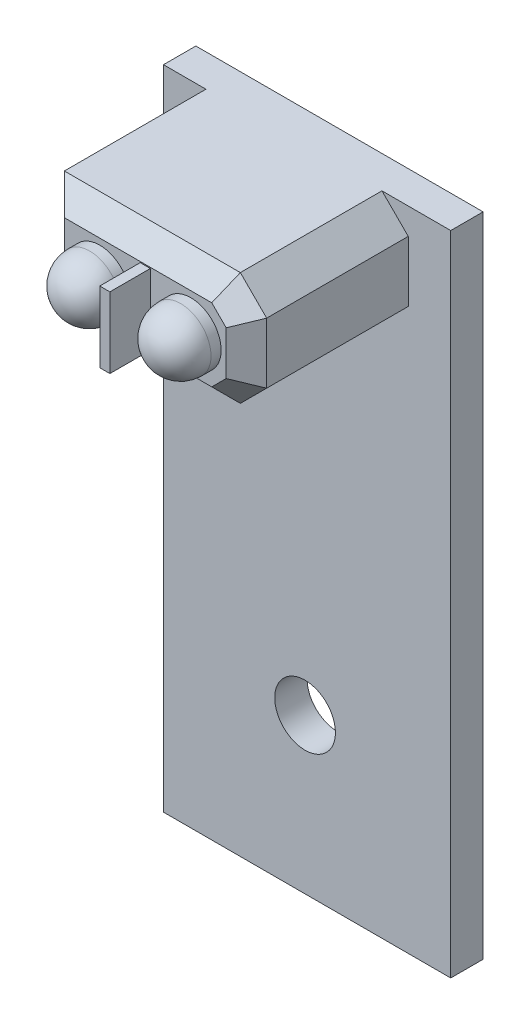
SolidWorks part; units mm, degrees
ref_plane "Alzado" through (0, 0, 0) normal (0, 0, 1) x (1, 0, 0)
ref_plane "Planta" through (0, 0, 0) normal (0, 1, 0) x (1, 0, 0)
ref_plane "Vista lateral" through (0, 0, 0) normal (1, 0, 0) x (0, 0, -1)
sketch "Croquis1" plane through (0, 0, 0) normal (0, 0, 1) x (1, 0, 0)
  line L1 (-7.1, -16) -> (7.1, -16)
  line L2 (-7.1, -16) -> (-7.1, 16)
  line L3 (-7.1, 16) -> (7.1, 16)
  line L4 (7.1, -16) -> (7.1, 16)
  line L5 (-7.1, -16) -> (7.1, 16) construction
  line L6 (-7.1, 16) -> (7.1, -16) construction
  point P0 (0, 0)
  dimension "D1" = 32
  dimension "D2" = 14.2
extrude "Saliente-Extruir1" add sketch "Croquis1" along normal blind 1.6
sketch "Croquis2" plane through (0, 0, 1.6) normal (0, 0, 1) x (1, 0, 0)
  line L0 (-7.1, -16) -> (7.1, -16) construction
  line L1 (-7.1, 16) -> (-7.1, -16) construction
  circle A0 centre (-0.1, -8.35) radius 1.5
  dimension "D1" = 3
  dimension "D2" = 7.65
  dimension "D3" = 7
extrude "Cortar-Extruir1" cut sketch "Croquis2" against normal through all
sketch "Croquis3" plane through (0, 0, 1.6) normal (0, 0, 1) x (1, 0, 0)
  line L0 (7.1, 16) -> (-7.1, 16) construction
  line L1 (-5, 16) -> (3.7, 16)
  line L2 (-5, 16) -> (-5, 10.4)
  line L3 (-5, 10.4) -> (3.7, 10.4)
  line L4 (5, 14.7) -> (5, 11.7)
  line L5 (-5, 16) -> (3.9571, 10.6571) construction
  line L6 (-5, 10.4) -> (4.3862, 15.3138) construction
  line L7 (5, 14.7) -> (3.7, 16)
  line L8 (5, 11.7) -> (3.7, 10.4)
  line L9 (-7.1, 16) -> (-7.1, -16) construction
  line L10 (7.1, -16) -> (7.1, 16) construction
  point P0 (0, 13.0175)
  dimension "D1" = 2.1
  dimension "D2" = 3.4
  dimension "D3" = 12.1
  dimension "D4" = 2.9825
  dimension "D5" = 4.3
extrude "Saliente-Extruir2" add sketch "Croquis3" along normal blind 10 contours L1 L7 L4 L8 L3 L2
sketch "Croquis4" plane through (0, 0, 11.6) normal (0, 0, 1) x (1, 0, 0)
  line L0 (-5, 10.4) -> (-5, 13.2) construction
  line L1 (-5, 16) -> (-5, 10.4) construction
  line L4 (0, 10.4) -> (-5, 10.4) construction
  line L5 (-5, 16) -> (-5, 10.4) construction
  line L6 (-5, 10.4) -> (3.7, 10.4) construction
  line L11 (-0.25, 14.95) -> (0.25, 14.95)
  line L12 (-0.25, 14.95) -> (-0.25, 11.45)
  line L13 (-0.25, 11.45) -> (0.25, 11.45)
  line L14 (0.25, 14.95) -> (0.25, 11.45)
  line L15 (-0.25, 14.95) -> (0.25, 11.45) construction
  line L16 (-5, 10.4) -> (3.7, 10.4)
  line L17 (3.7, 10.4) -> (5, 11.7)
  line L18 (5, 11.7) -> (5, 14.7)
  line L19 (5, 14.7) -> (3.7, 16)
  line L20 (3.7, 16) -> (-5, 16)
  line L21 (-5, 16) -> (-5, 10.4)
  line L22 (-5, 10.4) -> (3.7, 10.4)
  line L23 (3.7, 10.4) -> (5, 11.7)
  line L24 (5, 11.7) -> (5, 14.7)
  line L25 (5, 14.7) -> (3.7, 16)
  line L26 (3.7, 16) -> (-5, 16)
  line L27 (-5, 16) -> (-5, 10.4)
  line L28 (-0.25, 11.45) -> (0.25, 14.95) construction
  circle A0 centre (-2.25, 13.2) radius 1.5
  circle A1 centre (2.25, 13.2) radius 1.5
  point P18 (0, 13.2)
  dimension "D1" = 3
  dimension "D2" = 2.75
  dimension "D3" = 4.75
  dimension "D4" = 5
  dimension "D5" = 1.05
  dimension "D6" = 7.25
  dimension "D7" = 0
extrude "Cortar-Extruir2" cut sketch "Croquis4" against normal blind 2
chamfer "Chaflán1" distance 1 angle 45 6 edges at (4.35, 15.35, 9.6) (5, 13.2, 9.6) (4.35, 11.05, 9.6) (-0.65, 10.4, 9.6) (-5, 13.2, 9.6) (-0.65, 16, 9.6)
fillet "Redondeo1" radius 1.5 2 edges at (3.75, 13.2, 11.6) (-0.75, 13.2, 11.6)
sketch "Croquis5" plane through (0, 0, 0) normal (0, 0, -1) x (-1, 0, 0)
  line L1 (-0.4, -3) -> (6.6, -3)
  line L2 (-0.4, -3) -> (-0.4, 4)
  line L3 (-0.4, 4) -> (6.6, 4)
  line L4 (6.6, -3) -> (6.6, 4)
  line L5 (-0.4, -3) -> (6.6, 4) construction
  line L6 (-0.4, 4) -> (6.6, -3) construction
  line L7 (-7.1, -16) -> (-7.1, 16) construction
  line L8 (-7.1, 16) -> (7.1, 16) construction
  point P0 (3.1, 0.5)
  dimension "D1" = 7
  dimension "D2" = 6.7
  dimension "D3" = 12
extrude "Saliente-Extruir3" add sketch "Croquis5" along normal blind 5
